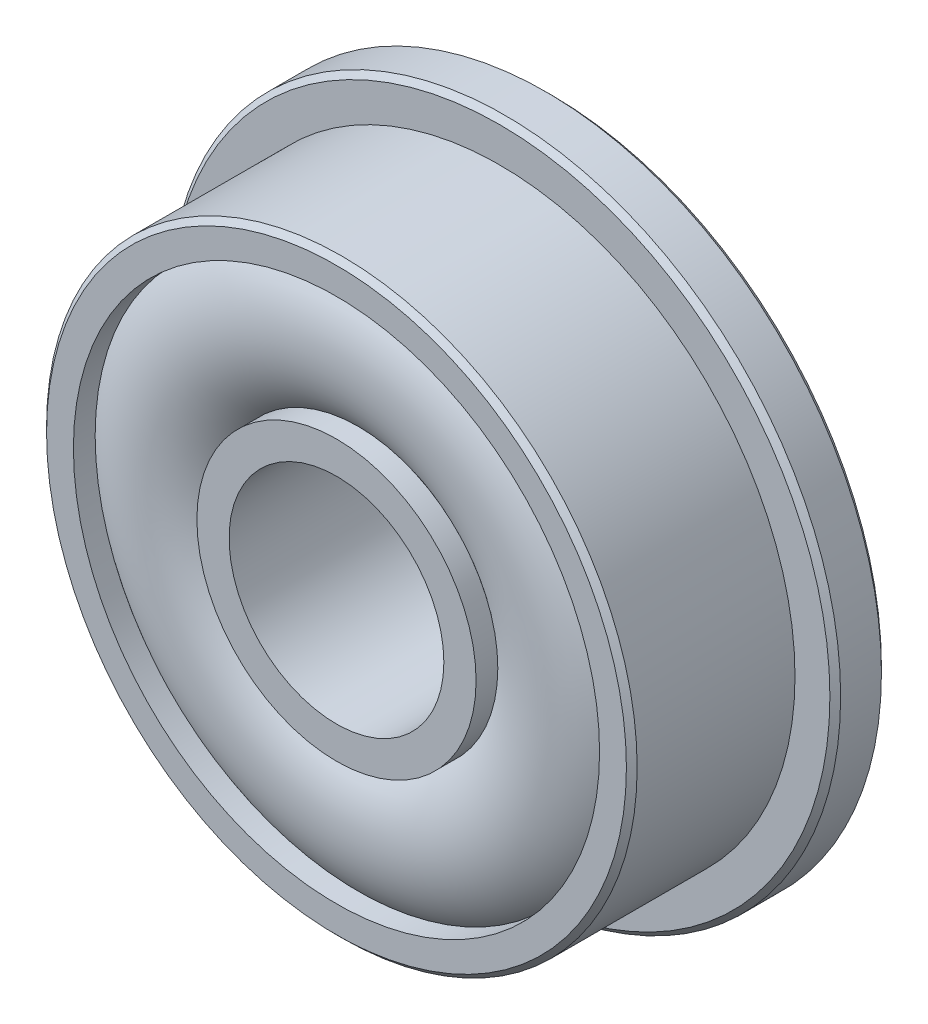
SolidWorks part; units mm, degrees
ref_plane "Спереди" through (0, 0, 0) normal (0, 0, 1) x (1, 0, 0)
ref_plane "Сверху" through (0, 0, 0) normal (0, 1, 0) x (1, 0, 0)
ref_plane "Справа" through (0, 0, 0) normal (1, 0, 0) x (0, 0, -1)
sketch "Sketch1" plane through (0, 0, 0) normal (1, 0, 0) x (0, 0, -1)
  line L0 (-2, 2) -> (2, 2)
  line L1 (2, 2) -> (2, 2.6)
  line L2 (0, 0) -> (9.4783, 0) construction
  line L3 (-2, 2) -> (-2, 2.6)
  line L4 (-2, 5.5) -> (1.04, 5.5)
  line L5 (1.04, 5.5) -> (1.04, 6.25)
  line L6 (1.04, 6.25) -> (2, 6.25)
  line L7 (-2, 2.6) -> (-1.595, 2.6)
  line L8 (-2, 4.9) -> (-1.595, 4.9)
  line L9 (-2, 4.9) -> (-2, 5.5)
  line L10 (2, 4.9) -> (2, 6.25)
  line L11 (1.595, 4.9) -> (2, 4.9)
  line L12 (1.595, 2.6) -> (2, 2.6)
  arc A0 (-1.595, 4.9) -> (-1.595, 2.6) centre (-0.165, 3.75) ccw
  arc A1 (1.595, 4.9) -> (1.595, 2.6) centre (0.165, 3.75) cw
  point P19 (0, 2)
  dimension "D1" = 4
  dimension "D2" = 12.5
  dimension "D3" = 4
  dimension "D4" = 11
  dimension "D5" = 0.96
  dimension "D6" = 0.6
  dimension "D7" = 0.6
revolve "Revolve1" add sketch "Sketch1" angle 360 about L2
chamfer "Chamfer1" distance 0.1 angle 45 3 edges at (6.25, 0, -2) (5.5, 0, 2) (6.25, 0, -1.04)
